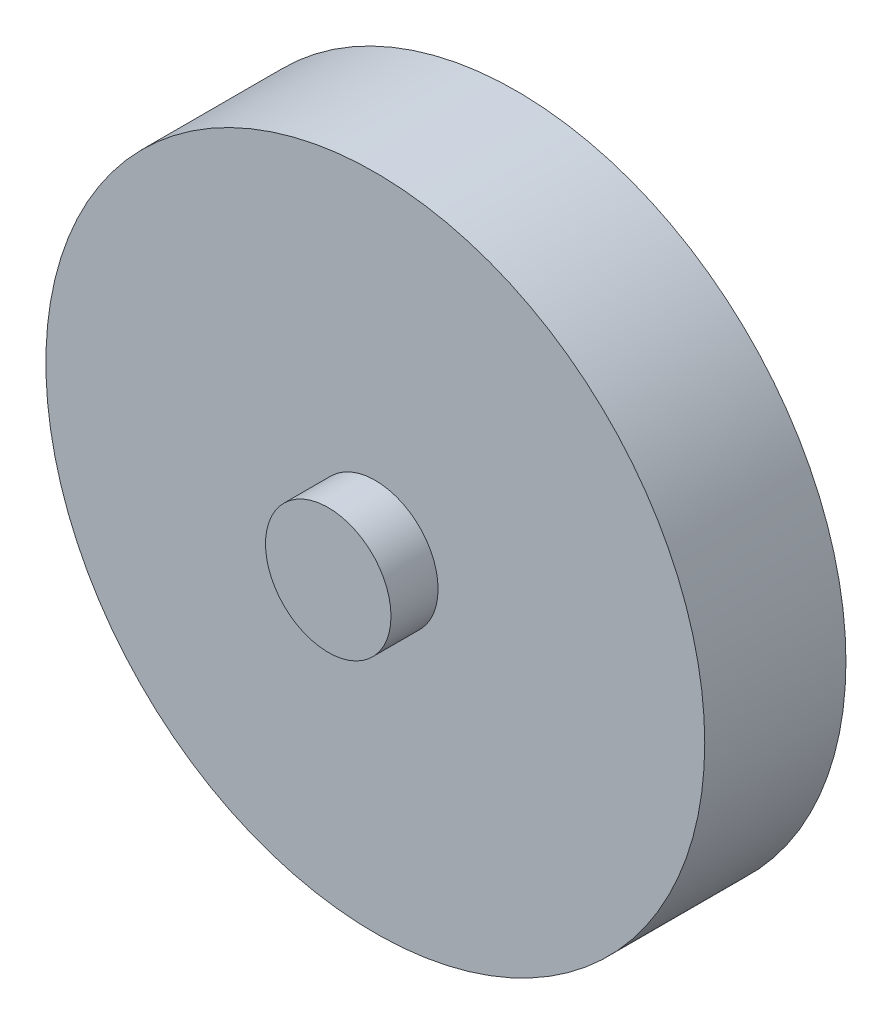
SolidWorks part; units mm, degrees
ref_plane "前视基准面" through (0, 0, 0) normal (0, 0, 1) x (1, 0, 0)
ref_plane "上视基准面" through (0, 0, 0) normal (0, 1, 0) x (1, 0, 0)
ref_plane "右视基准面" through (0, 0, 0) normal (1, 0, 0) x (0, 0, -1)
other "Configuration Table"
sketch "草图1" plane through (0, 0, 0) normal (0, 0, 1) x (1, 0, 0)
  circle A0 centre (0, 0) radius 8
extrude "凸台-拉伸1" add sketch "草图1" along normal blind 24
sketch "草图2" plane through (0, 0, 0) normal (0, 0, 1) x (1, 0, 0)
  circle A0 centre (0, 0) radius 42
extrude "凸台-拉伸2" add sketch "草图2" along normal blind 18
sketch "草图3" plane through (0, 0, 18) normal (0, 0, 1) x (1, 0, 0)
  line L0 (37.445, 2.0305) -> (37.5326, 2.0353)
  arc A0 (41.9927, 0.7845) -> (41.5984, 5.7942) centre (0, 0) ccw
  arc A1 (37.5326, 3.8521) -> (37.6744, 2.043) centre (0, 0) cw
